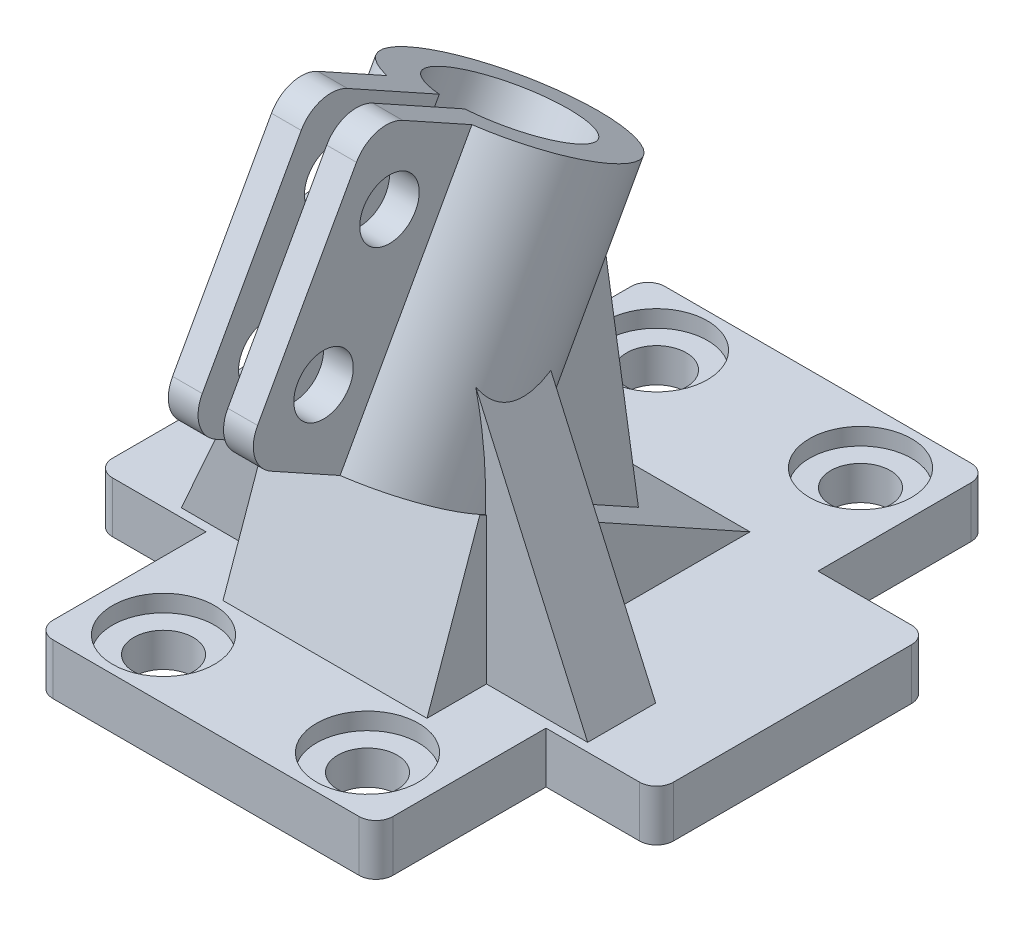
SolidWorks part; units mm, degrees
ref_plane "前视基准面" through (0, 0, 0) normal (0, 0, 1) x (1, 0, 0)
ref_plane "上视基准面" through (0, 0, 0) normal (0, 1, 0) x (1, 0, 0)
ref_plane "右视基准面" through (0, 0, 0) normal (1, 0, 0) x (0, 0, -1)
sketch "草图1" plane through (0, 0, 0) normal (0, 1, 0) x (1, 0, 0)
  line L1 (-10, -18) -> (10, -18)
  line L2 (-10, -18) -> (-10, 18)
  line L3 (-10, 18) -> (10, 18)
  line L4 (10, -18) -> (10, 18)
  line L5 (-10, -18) -> (10, 18) construction
  line L6 (-10, 18) -> (10, -18) construction
  point P0 (0, 0)
  dimension "D1" = 36
  dimension "D2" = 20
extrude "凸台-拉伸1" add sketch "草图1" along normal blind 3
sketch "草图2" plane through (0, 3, 0) normal (0, 1, 0) x (1, 0, 0)
  line L1 (-16.5, -8) -> (16.5, -8)
  line L2 (-16.5, -8) -> (-16.5, 8)
  line L3 (-16.5, 8) -> (16.5, 8)
  line L4 (16.5, -8) -> (16.5, 8)
  line L5 (-16.5, -8) -> (16.5, 8) construction
  line L6 (-16.5, 8) -> (16.5, -8) construction
  point P0 (0, 0)
  dimension "D1" = 16
  dimension "D2" = 33
extrude "凸台-拉伸2" add sketch "草图2" against normal blind 3
sketch "草图9" plane through (0, 0, 0) normal (1, 0, 0) x (0, 0, -1)
  line L0 (-11, 3) -> (-7.8903, 11.8082)
  line L1 (-18, 3) -> (-8, 3) construction
  line L2 (-7.8903, 11.8082) -> (8, 3)
  line L3 (8, 3) -> (-11, 3)
  line L4 (-18, 3) -> (-18, 0) construction
  dimension "D1" = 7
  dimension "D2" = 29
extrude "凸台-拉伸4" add sketch "草图9" along normal mid plane 12
sketch "草图11" plane through (0, 5.6871, -3.1524) normal (0, 0.8746, -0.4848) x (1, 0, 0)
  line L0 (2.5, -24.6839) -> (-2.5, -24.6839) construction
  line L1 (2.5, -24.6839) -> (2.5, -15.6839) construction
  line L2 (2.5, -15.6839) -> (-2.5, -15.6839) construction
  line L3 (-2.5, -24.6839) -> (-2.5, -15.6839) construction
  line L4 (2.5, -24.6839) -> (-2.5, -15.6839) construction
  line L5 (2.5, -15.6839) -> (-2.5, -24.6839) construction
  line L6 (0.75, -24.6839) -> (2.5, -24.6839)
  line L7 (0.75, -24.6839) -> (0.75, -15.6839)
  line L8 (0.75, -15.6839) -> (2.5, -15.6839)
  line L9 (2.5, -24.6839) -> (2.5, -15.6839)
  line L10 (0.75, -24.6839) -> (2.5, -15.6839) construction
  line L11 (0.75, -15.6839) -> (2.5, -24.6839) construction
  line L12 (-0.75, -24.6839) -> (-2.5, -24.6839)
  line L13 (-0.75, -24.6839) -> (-0.75, -15.6839)
  line L14 (-0.75, -15.6839) -> (-2.5, -15.6839)
  line L15 (-2.5, -24.6839) -> (-2.5, -15.6839)
  line L16 (-0.75, -24.6839) -> (-2.5, -15.6839) construction
  line L17 (-0.75, -15.6839) -> (-2.5, -24.6839) construction
  line L18 (6, -12.6257) -> (-6, -12.6257) construction
  circle A0 centre (0, -12.6257) radius 3.95
  circle A1 centre (0, -12.6257) radius 5.95
  point P2 (0, -8.6757)
  point P3 (0, -6.6757)
  point P5 (0, -20.1839)
  point P10 (0, -24.792)
  point P11 (1.625, -20.1839)
  point P12 (-1.625, -20.1839)
  line M1 (-6, 5.5425) -> (-6, -12.6257)
  line M2 (-6, -12.6257) -> (6, -12.6257)
  line M3 (6, -12.6257) -> (6, 5.5425)
  dimension "D1" = 7.9
  dimension "D2" = 2
  dimension "D3" = 5
  dimension "D4" = 1.5
  dimension "D5" = 9
  dimension "D6" = 0.75
extrude "凸台-拉伸6" add sketch "草图11" along normal blind 16 contours L9 A1 A0 M3 M2 | A1 A0 M3 M1 M2 | A1 L15 A0 M1 M2 | L7 A1 L9 A0 | L15 A1 L13 A0 | A1 L15 L12 L13 | A1 L7 L6 L9
sketch "草图12" plane through (0, 0, 0) normal (1, 0, 0) x (0, 0, -1)
  line L1 (-4.4356, 9.8932) -> (1.3821, 20.3886)
  line L2 (1.3821, 20.3886) -> (3.436, 5.5299)
  line L3 (8, 3) -> (-7.8903, 11.8082) construction
  line L4 (3.436, 5.5299) -> (-4.4356, 9.8932)
  dimension "D1" = 9
  dimension "D2" = 12
extrude "凸台-拉伸7" add sketch "草图12" along normal mid plane 8
sketch "草图13" plane through (2.5, 0, 0) normal (1, 0, 0) x (0, 0, -1)
  line L0 (-7.7677, 30.0339) -> (-15.5247, 16.0399) construction
  line L1 (-10.6797, 31.648) -> (-4.8557, 28.4197) construction
  line L2 (-18.4367, 17.6541) -> (-12.6127, 14.4258) construction
  line L3 (-14.5582, 24.651) -> (-8.7342, 21.4227) construction
  line L4 (-10.6797, 31.648) -> (-18.4367, 17.6541) construction
  line L5 (-4.8557, 28.4197) -> (-12.6127, 14.4258) construction
  circle A0 centre (-9.707, 26.5354) radius 1.75
  circle A1 centre (-13.5854, 19.5384) radius 1.75
  dimension "D1" = 3.5
  dimension "D2" = 4
extrude "切除-拉伸4" cut sketch "草图13" against normal through all
fillet "圆角3" radius 2 4 edges at (-1.625, 17.6541, 18.4367) (-1.625, 31.648, 10.6797) (1.625, 17.6541, 18.4367) (1.625, 31.648, 10.6797)
fillet "圆角5" radius 1 8 edges at (-16.5, 1.5, -8) (-16.5, 1.5, 8) (-10, 1.5, 18) (10, 1.5, 18) (16.5, 1.5, 8) (16.5, 1.5, -8) (-10, 1.5, -18) (10, 1.5, -18)
sketch "草图14" plane through (0, 3, 0) normal (0, 1, 0) x (1, 0, 0)
  circle A0 centre (-6, -14.5) radius 1.75
  circle A1 centre (-6, 14.5) radius 1.75
  circle A2 centre (6, 14.5) radius 1.75
  circle A3 centre (6, -14.5) radius 1.75
extrude "切除-拉伸5" cut sketch "草图14" against normal through all
sketch "草图15" plane through (0, 3, 0) normal (0, 1, 0) x (1, 0, 0)
  circle A0 centre (6, -14.5) radius 3
  circle A1 centre (-6, -14.5) radius 3
  circle A2 centre (6, 14.5) radius 3
  circle A3 centre (-6, 14.5) radius 3
extrude "切除-拉伸6" cut sketch "草图15" against normal blind 1
ref_plane "基准面1" through (0, 0, 5.5) normal (0, 0, -1) x (-1, 0, 0)
sketch "草图16" plane through (0, 0, 5.5) normal (0, 0, -1) x (-1, 0, 0)
  line L0 (0, 29.9547) -> (0, 0) construction
  line L1 (-3.95, 21) -> (-11.95, 3)
  line L2 (-15.5, 3) -> (-10, 3) construction
  line L3 (-11.95, 3) -> (-3.95, 3)
  line L4 (-9, 3) -> (9, 3) construction
  line L5 (-3.95, 3) -> (-3.95, 21)
  line L6 (-5.95, 25.8021) -> (-5.95, 11.8082) construction
  line L7 (3.95, 3) -> (3.95, 21)
  line L8 (11.95, 3) -> (3.95, 3)
  line L9 (3.95, 21) -> (11.95, 3)
  dimension "D1" = 8
  dimension "D2" = 18
  dimension "D3" = 2
extrude "凸台-拉伸8" add sketch "草图16" along normal mid plane 4
